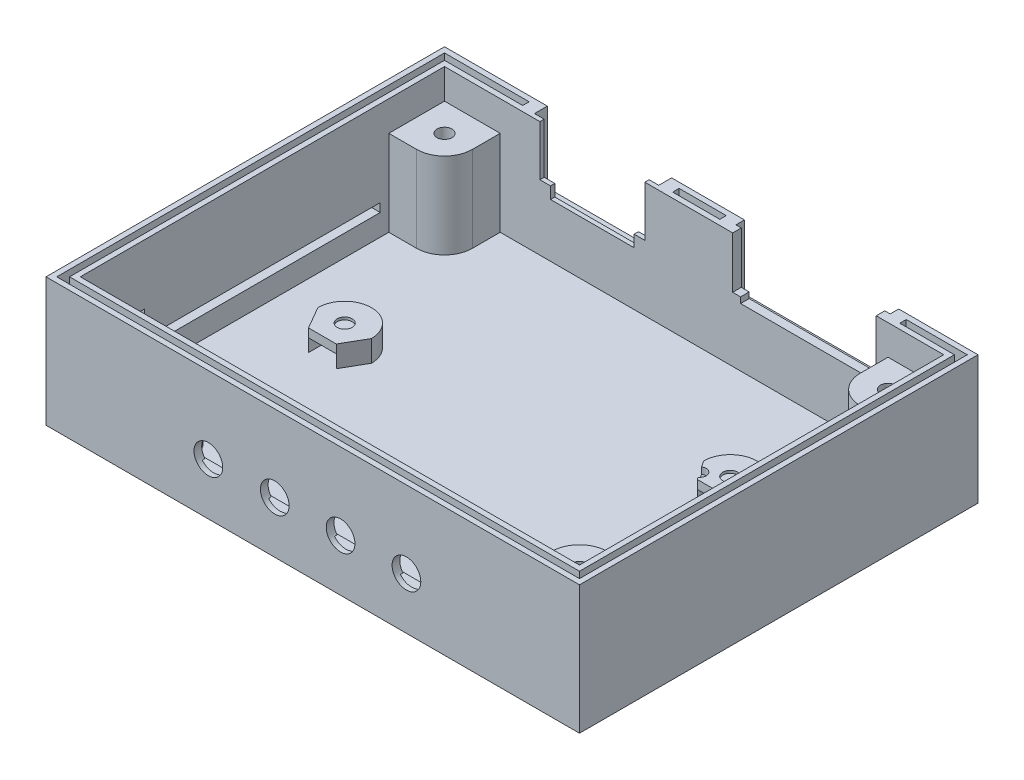
SolidWorks part; units mm, degrees
ref_plane "Спереди" through (0, 0, 0) normal (0, 0, 1) x (1, 0, 0)
ref_plane "Сверху" through (0, 0, 0) normal (0, 1, 0) x (1, 0, 0)
ref_plane "Справа" through (0, 0, 0) normal (1, 0, 0) x (0, 0, -1)
sketch "Эскиз1" plane through (0, 0, 0) normal (0, 1, 0) x (1, 0, 0)
  line L1 (-58.25, -42.5) -> (58.25, -42.5)
  line L2 (-58.25, -42.5) -> (-58.25, 42.5)
  line L3 (-58.25, 42.5) -> (58.25, 42.5)
  line L4 (58.25, -42.5) -> (58.25, 42.5)
  line L5 (-58.25, -42.5) -> (58.25, 42.5) construction
  line L6 (-58.25, 42.5) -> (58.25, -42.5) construction
  point P0 (0, 0)
  dimension "D1" = 116.5
  dimension "D2" = 85
extrude "Бобышка-Вытянуть1" add sketch "Эскиз1" along normal blind 3
sketch "Эскиз3" plane through (0, 3, 0) normal (0, 1, 0) x (1, 0, 0)
  line L0 (-58.25, 42.5) -> (-58.25, -42.5) construction
  line L1 (-36.8, -40.5) -> (-38.425, -37.6854) construction
  line L2 (-38.425, -37.6854) -> (-41.675, -37.6854) construction
  line L3 (-41.675, -37.6854) -> (-43.3, -40.5) construction
  line L4 (-43.3, -40.5) -> (-41.675, -43.3146) construction
  line L5 (-41.675, -43.3146) -> (-38.425, -43.3146) construction
  line L6 (-38.425, -43.3146) -> (-36.8, -40.5) construction
  line L7 (-58.25, -42.5) -> (58.25, -42.5) construction
  line L8 (-46.3, -40.5) -> (-46.3, -42.5)
  line L9 (-46.3, -40.5) -> (-43.3, -35.3038)
  line L10 (-33.8, -42.5) -> (-33.8, -40.5)
  line L11 (-43.3, -35.3038) -> (-43.3, -40.5)
  line L12 (-43.3, -40.5) -> (-91.5414, -40.5) construction
  line L13 (-33.8, -40.5) -> (-36.8, -40.5) construction
  line L14 (-36.8, -40.5) -> (-36.8, -35.3038)
  line L15 (-33.8, -40.5) -> (-36.8, -35.3038)
  line L19 (32.7, -40.5) -> (34.325, -43.3146) construction
  line L21 (34.325, -43.3146) -> (37.575, -43.3146) construction
  line L22 (37.575, -43.3146) -> (39.2, -40.5) construction
  line L23 (39.2, -40.5) -> (39.2, -35.3038)
  line L31 (-43.3, 1) -> (-46.3, 1) construction
  line L32 (-36.8, 1) -> (-38.425, 3.8146)
  line L33 (-38.425, 3.8146) -> (-41.675, 3.8146)
  line L34 (-41.675, 3.8146) -> (-43.3, 1)
  line L35 (-43.3, 1) -> (-41.675, -1.8146) construction
  line L36 (-41.675, -1.8146) -> (-38.425, -1.8146) construction
  line L37 (-38.425, -1.8146) -> (-36.8, 1) construction
  line L38 (-40.05, 3.8146) -> (-40.05, -1.8146) construction
  line L39 (-46.3, 1) -> (-43.3, -4.1962)
  line L40 (-43.3, -4.1962) -> (-43.3, 1)
  line L41 (-36.8, 1) -> (-33.8, 1) construction
  line L42 (-33.8, 1) -> (-36.8, -4.1962)
  line L43 (-36.8, -4.1962) -> (-36.8, 1)
  line L44 (35.95, 15) -> (-41.0381, 65.945) construction
  line L57 (42.2, -40.5) -> (39.2, -35.3038)
  line L58 (42.2, -42.5) -> (42.2, -40.5)
  line L60 (29.7, -40.5) -> (29.7, -42.5)
  line L61 (29.7, -40.5) -> (32.7, -35.3038)
  line L62 (32.7, -35.3038) -> (32.7, -40.5)
  line L67 (-46.3, -42.5) -> (-42.1453, -42.5)
  line L68 (-33.8, -42.5) -> (-37.9547, -42.5)
  line L69 (-42.1453, -42.5) -> (-43.3, -40.5)
  line L70 (-37.9547, -42.5) -> (-36.8, -40.5)
  line L71 (29.7, -42.5) -> (33.8547, -42.5)
  line L72 (42.2, -42.5) -> (38.0453, -42.5)
  line L73 (33.8547, -42.5) -> (32.7, -40.5)
  line L74 (38.0453, -42.5) -> (39.2, -40.5)
  line L76 (32.7, 15) -> (29.7, 15) construction
  line L77 (39.2, 15) -> (37.3861, 17.6967)
  line L78 (37.3861, 17.6967) -> (34.5139, 17.6967)
  line L79 (34.5139, 17.6967) -> (32.7, 15)
  line L80 (32.7, 15) -> (34.5139, 12.3033) construction
  line L81 (34.5139, 12.3033) -> (37.3861, 12.3033) construction
  line L82 (37.3861, 12.3033) -> (39.2, 15) construction
  line L83 (35.95, 17.6967) -> (35.95, 12.3033) construction
  line L84 (29.7, 15) -> (32.7, 10.5398)
  line L85 (32.7, 10.5398) -> (32.7, 15)
  line L86 (39.2, 15) -> (42.2, 15) construction
  line L87 (42.2, 15) -> (39.2, 10.5398)
  line L88 (39.2, 10.5398) -> (39.2, 15)
  line L89 (32.7, 10.5398) -> (19.4042, 10.5398) construction
  circle A0 centre (-40.05, -40.5) radius 2.8146 construction
  circle A2 centre (-40.05, 1) radius 2.8146 construction
  circle A4 centre (35.95, 15) radius 2.6967 construction
  arc A6 (-46.3, 1) -> (-33.8, 1) centre (-40.05, 1) cw
  arc A7 (29.7, 15) -> (42.2, 15) centre (35.95, 15) cw
  dimension "D1" = 6.5
  dimension "D17" = 6.25
  dimension "D18" = 6.25
  dimension "D2" = 18.2
  dimension "D3" = 2
  dimension "D4" = 3
  dimension "D5" = 3
  dimension "D7" = 18.2
  dimension "D8" = 43.5
  dimension "D9" = 6.5
  dimension "D10" = 3
  dimension "D11" = 3
  dimension "D12" = 57.5
  dimension "D13" = 94.2
  dimension "D14" = 6.5
  dimension "D15" = 3
  dimension "D16" = 3
  dimension "D6" = 2
extrude "Бобышка-Вытянуть2" add sketch "Эскиз3" along normal blind 3
sketch "Эскиз4" plane through (0, 6, 0) normal (0, 1, 0) x (1, 0, 0)
  line L2 (-33.8, -40.5) -> (-36.8, -35.3038)
  line L3 (-36.8, -35.3038) -> (-43.3, -35.3038)
  line L4 (-43.3, -35.3038) -> (-46.3, -40.5)
  line L6 (-46.3, 1) -> (-43.3, -4.1962)
  line L7 (-43.3, -4.1962) -> (-36.8, -4.1962)
  line L8 (-36.8, -4.1962) -> (-33.8, 1)
  line L9 (29.7, 15) -> (32.7, 10.5398)
  line L10 (32.7, 10.5398) -> (39.2, 10.5398)
  line L11 (39.2, 10.5398) -> (42.2, 15)
  line L12 (29.7, -40.5) -> (29.7, -42.5)
  line L15 (42.2, -40.5) -> (39.2, -35.3038)
  line L16 (39.2, -35.3038) -> (32.7, -35.3038)
  line L17 (32.7, -35.3038) -> (29.7, -40.5)
  line L18 (32.7, -40.5) -> (39.2, -40.5) construction
  line L19 (-43.3, -40.5) -> (-36.8, -40.5) construction
  line L25 (-46.3, -40.5) -> (-46.3, -42.5)
  line L26 (-46.3, -42.5) -> (-33.8, -42.5)
  line L27 (-33.8, -42.5) -> (-33.8, -40.5)
  line L28 (29.7, -42.5) -> (42.2, -42.5)
  line L29 (42.2, -42.5) -> (42.2, -40.5)
  line L30 (29.7, 15) -> (42.2, 15) construction
  line L31 (-46.3, 1) -> (-33.8, 1) construction
  line L32 (-36.8, 1) -> (-36.8, -4.1962) construction
  arc A0 (-46.3, 1) -> (-33.8, 1) centre (-40.05, 1) cw
  arc A1 (29.7, 15) -> (42.2, 15) centre (35.95, 15) cw
  circle A2 centre (35.95, -40.5) radius 1.6 construction
  circle A3 centre (35.95, 15) radius 1.6 construction
  circle A4 centre (-40.05, 1) radius 1.6 construction
  circle A5 centre (-40.05, -40.5) radius 1.6 construction
  arc A7 (-33.8, 1) -> (-46.3, 1) centre (-40.05, 1) ccw construction
  point P2 (-36.8, -4.1962)
  dimension "D1" = 3.2
extrude "Бобышка-Вытянуть3" add sketch "Эскиз4" along normal blind 2
sketch3d "Трехмерный эскиз1"
  line L0 (-60.05, 3, 45) -> (-52.2057, 3, 31.4133)
  line L1 (-58.25, 3, 42.5) -> (-46.3, 3, 42.5) construction
  line L2 (-60.05, 3, 50.197) -> (-60.05, 3, 53.4146) construction
  line L4 (-58.25, 3, -42.5) -> (-58.25, 3, 42.5) construction
  dimension "D1" = 60
  dimension "D2" = 1.8
  dimension "D3" = 2.5
ref_plane "Плоскость1" through (-25.5519, 0, -14.7524) normal (0.866, 0, 0.5) x (0.5, 0, -0.866)
sketch "Эскиз5" plane through (0, 8, 0) normal (0, 1, 0) x (1, 0, 0)
  line L1 (-33.8, -40.5) -> (-36.8, -35.3038) construction
  line L2 (-35.8, -37.0359) -> (-33.8, -37.0359)
  line L3 (-33.8, -37.0359) -> (-33.8, -42.5)
  line L5 (35.7, -35.3038) -> (35.7, -36.8038)
  line L6 (39.2, -35.3038) -> (32.7, -35.3038) construction
  line L7 (35.7, -36.8038) -> (37.2, -36.8038)
  line L8 (37.2, -36.8038) -> (37.2, -35.3038)
  line L9 (37.2, -35.3038) -> (35.7, -35.3038)
  line L10 (29.7, 15) -> (32.7, 10.5398) construction
  line L11 (30.6656, 13.5644) -> (32.3399, 11.0751)
  line L12 (-35.8, -37.0359) -> (-35.8, -42.5)
  line L13 (-46.3, -42.5) -> (-33.8, -42.5) construction
  line L14 (-35.8, -42.5) -> (-33.8, -42.5)
  arc A0 (30.6656, 13.5644) -> (32.3399, 11.0751) centre (31.5027, 12.3198) cw
  point P0 (-35.8, -37.0359)
  dimension "D5" = 1.5
  dimension "D1" = 2
  dimension "D2" = 1.5
  dimension "D3" = 2
  dimension "D4" = 1.78
  dimension "D6" = 0
  dimension "D7" = 1.5
extrude "Вырез-Вытянуть1" cut sketch "Эскиз5" against normal blind 1.5
sketch "Эскиз211" plane through (0, 8, 0) normal (0, 1, 0) x (1, 0, 0)
  line L0 (29.7, -40.5) -> (42.2, -40.5) construction
  line L1 (-46.3, -40.5) -> (-33.8, -40.5) construction
  circle A0 centre (-40.05, 1) radius 1.75
  circle A1 centre (35.95, 15) radius 1.75
  circle A2 centre (35.95, -40.5) radius 1.75
  circle A3 centre (-40.05, -40.5) radius 1.75
  point P18 (42.2, -40.5)
  point P20 (-33.8, -40.5)
  dimension "D1" = 3.5
  dimension "D2" = 3.5
  dimension "D3" = 3.5
  dimension "D4" = 3.5
extrude "Вырез-Вытянуть17" cut sketch "Эскиз211" against normal blind 0.6
sketch "Эскиз6" plane through (0, 3, 0) normal (0, 1, 0) x (1, 0, 0)
  line L2 (58.25, -42.5) -> (58.25, 42.5)
  line L3 (58.25, 42.5) -> (-58.25, 42.5)
  line L5 (-58.25, -42.5) -> (58.25, -42.5)
  line L6 (-58.25, 42.5) -> (-58.25, -42.5)
extrude "Вытянуть-Тонкостенный1" add sketch "Эскиз6" along normal blind 27 and the other way blind 3 thin
sketch "Эскиз29" plane through (0, 3, 0) normal (0, 1, 0) x (1, 0, 0)
  line L0 (-35.8, -37.0359) -> (-36.8, -35.3038) construction
  line L1 (-36.8, -40.5) -> (-38.425, -37.6854)
  line L2 (-38.425, -37.6854) -> (-41.675, -37.6854)
  line L3 (-41.675, -37.6854) -> (-43.3, -40.5)
  line L4 (-43.3, -40.5) -> (-41.675, -43.3146)
  line L5 (-41.675, -43.3146) -> (-38.425, -43.3146)
  line L6 (-38.425, -43.3146) -> (-36.8, -40.5)
  line L7 (39.2, -40.5) -> (37.575, -37.6854)
  line L8 (37.575, -37.6854) -> (34.325, -37.6854)
  line L9 (34.325, -37.6854) -> (32.7, -40.5)
  line L10 (32.7, -40.5) -> (34.325, -43.3146)
  line L11 (34.325, -43.3146) -> (37.575, -43.3146)
  line L12 (37.575, -43.3146) -> (39.2, -40.5)
  line L13 (-43.3, -35.3038) -> (-46.3, -40.5) construction
  line L15 (42.2, -40.5) -> (39.2, -35.3038) construction
  line L16 (32.7, -35.3038) -> (29.7, -40.5) construction
  circle A0 centre (-40.05, -40.5) radius 2.8146 construction
  circle A1 centre (35.95, -40.5) radius 2.8146 construction
  dimension "D1" = 6.5
  dimension "D2" = 6.5
  dimension "D3" = 2.5981
  dimension "D4" = 2.5981
  dimension "D5" = 2.5981
  dimension "D6" = 2.5981
extrude "Вырез-Вытянуть6" cut sketch "Эскиз29" along normal blind 3
ref_plane "Плоскость2" through (0, 8, 0) normal (0, 1, 0) x (1, 0, 0)
sketch "Эскиз9" plane through (0, 8, 0) normal (0, 1, 0) x (1, 0, 0)
  line L0 (-58.25, -42.5) -> (46.75, -42.5)
  line L2 (-58.25, -42.5) -> (-58.25, 27.5)
  line L4 (-60.05, 199949.803) -> (-60.05, -200053.4146) construction
  line L5 (42.2, -42.5) -> (58.25, -42.5) construction
  dimension "D1" = 105
  dimension "D2" = 70
extrude "Вырез-Вытянуть-Тонкостенный1" cut sketch "Эскиз9" along normal blind 2 thin
sketch "Эскиз30" plane through (0, 0, 42.5) normal (0, 0, -1) x (-1, 0, 0)
  line L0 (58.25, 12.1) -> (33.0029, 12.1) construction
  line L2 (58.25, 3) -> (46.3, 3) construction
  line L3 (58.25, 10) -> (58.25, 30) construction
  circle A0 centre (24.363, 12.1) radius 3.35
  circle A1 centre (8.869, 12.1) radius 3.35
  circle A2 centre (-6.498, 12.1) radius 3.35
  circle A3 centre (-21.865, 12.1) radius 3.35
  dimension "D2" = 6.7
  dimension "D4" = 6.7
  dimension "D8" = 6.7
  dimension "D9" = 6.7
  dimension "D1" = 9.1
  dimension "D3" = 33.887
  dimension "D5" = 49.381
  dimension "D6" = 64.748
  dimension "D7" = 80.115
extrude "Вырез-Вытянуть7" cut sketch "Эскиз30" against normal up to surface (4 mm away) up to face at (0, 15, 46.5)
sketch "Эскиз31" plane through (0, 0, 42.5) normal (0, 0, -1) x (-1, 0, 0)
  line L1 (17.763, 8.6) -> (30.963, 8.6)
  line L2 (17.763, 8.6) -> (17.763, 15.6)
  line L3 (17.763, 15.6) -> (30.963, 15.6)
  line L4 (30.963, 8.6) -> (30.963, 15.6)
  line L5 (17.763, 8.6) -> (30.963, 15.6) construction
  line L6 (17.763, 15.6) -> (30.963, 8.6) construction
  line L7 (2.269, 8.6) -> (15.469, 8.6)
  line L8 (2.269, 8.6) -> (2.269, 15.6)
  line L9 (2.269, 15.6) -> (15.469, 15.6)
  line L10 (15.469, 8.6) -> (15.469, 15.6)
  line L11 (2.269, 8.6) -> (15.469, 15.6) construction
  line L12 (2.269, 15.6) -> (15.469, 8.6) construction
  line L13 (-13.098, 8.6) -> (0.102, 8.6)
  line L14 (-13.098, 8.6) -> (-13.098, 15.6)
  line L15 (-13.098, 15.6) -> (0.102, 15.6)
  line L16 (0.102, 8.6) -> (0.102, 15.6)
  line L17 (-13.098, 8.6) -> (0.102, 15.6) construction
  line L18 (-13.098, 15.6) -> (0.102, 8.6) construction
  line L19 (-28.465, 8.6) -> (-15.265, 8.6)
  line L20 (-28.465, 8.6) -> (-28.465, 15.6)
  line L21 (-28.465, 15.6) -> (-15.265, 15.6)
  line L22 (-15.265, 8.6) -> (-15.265, 15.6)
  line L23 (-28.465, 8.6) -> (-15.265, 15.6) construction
  line L24 (-28.465, 15.6) -> (-15.265, 8.6) construction
  point P0 (24.363, 12.1)
  point P6 (8.869, 12.1)
  point P12 (-6.498, 12.1)
  point P18 (-21.865, 12.1)
  dimension "D1" = 13.2
  dimension "D2" = 13.2
  dimension "D3" = 13.2
  dimension "D4" = 13.2
  dimension "D5" = 7
  dimension "D6" = 7
  dimension "D7" = 7
  dimension "D8" = 7
extrude "Вырез-Вытянуть8" cut sketch "Эскиз31" against normal blind 2.2
sketch3d "Трехмерный эскиз3"
  line L0 (-12.2167, 12.2244, 46.5) -> (-8.869, 12.1, 46.5) construction
  line L1 (-24.363, 12.1, 46.5) -> (-27.7109, 12.2198, 46.5) construction
  line L2 (-24.363, 12.1, 44.57) -> (-18.4622, 12.1, 34.3495)
  line L3 (20.737, 12.1, 46.5) -> (-69.463, 12.1, 46.5) construction
  line L4 (-24.363, 12.1, 46.5) -> (-24.363, 12.1, 47.1668) construction
  line L5 (-8.869, 12.1, 45.3) -> (-8.869, 12.1, 44.7) construction
  line L6 (-8.869, 12.1, 44.57) -> (-2.4822, 12.1, 33.5078)
  line L9 (-27.7053, 12.3268, 46.5) -> (-24.363, 12.1, 46.5) construction
  line L10 (-24.363, 12.1, 45.3) -> (-24.363, 12.1, 44.7) construction
  line L11 (-24.363, 12.1, 44.57) -> (-21.013, 12.1, 46.5) construction
  line L12 (-8.869, 12.1, 46.5) -> (-8.869, 12.1, 45.6691) construction
  line L13 (3.1501, 12.2183, 46.5) -> (6.498, 12.1, 46.5) construction
  line L14 (6.498, 12.1, 45.3) -> (6.498, 12.1, 44.7) construction
  line L15 (18.5183, 12.2495, 46.5) -> (21.865, 12.1, 46.5) construction
  line L16 (21.865, 12.1, 45.3) -> (21.865, 12.1, 44.7) construction
  line L17 (6.498, 12.1, 46.5) -> (6.498, 12.1, 44.57) construction
  line L18 (21.865, 12.1, 46.5) -> (21.865, 12.1, 44.57) construction
  line L19 (6.498, 12.1, 44.57) -> (11.4556, 12.1, 35.9831)
  line L20 (21.865, 12.1, 44.57) -> (26.1469, 12.1, 37.1535)
  circle A0 centre (-24.363, 12.1, 46.5) radius 3.35 construction
  circle A1 centre (-8.869, 12.1, 46.5) radius 3.35 construction
  circle A2 centre (6.498, 12.1, 46.5) radius 3.35 construction
  circle A3 centre (21.865, 12.1, 46.5) radius 3.35 construction
  point P10 (-24.363, 12.1, 43.15)
  point P14 (-8.869, 12.1, 43.15)
  point P28 (6.498, 12.1, 43.15)
  point P35 (21.865, 12.1, 43.15)
  point P42 (0, 0, 0)
  point P43 (0.8434, 12.1, 36.2693)
  point P44 (13.0277, 12.1, 37.1042)
  point P45 (27.6053, 12.1, 38.2107)
  point P46 (-24.363, 12.1, 43.9721)
  point P47 (-18.7221, 12.1, 34.2038)
  dimension "D1" = 1.93
  dimension "D3" = 60
  dimension "D2" = 0
  dimension "D4" = 60
  dimension "D6" = 60
  dimension "D5" = 3.35
  dimension "D7" = 1.93
  dimension "D8" = 1.93
  dimension "D9" = 1.93
  dimension "D10" = 60
sweep "Вырез-По траектории1" cut path "Трехмерный эскиз3" circular profile diameter 7.7 parameters "D3"=7.7
curve "Кривая1"
sweep "Вырез-По траектории3" cut path "Кривая1" circular profile diameter 7.7 parameters "D3"=7.7
curve "Кривая2"
curve "Кривая3"
sweep "Вырез-По траектории4" cut path "Кривая2" circular profile diameter 7.7 parameters "D3"=7.7
sweep "Вырез-По траектории5" cut path "Кривая3" circular profile diameter 7.7 parameters "D3"=7.7
sketch "Эскиз121" plane through (-58.25, 0, 0) normal (1, 0, 0) x (0, 0, -1)
  line L0 (-42.5, 12.1) -> (-38.102, 12.1) construction
  line L1 (-42.5, 10) -> (-42.5, 30) construction
  line L2 (42.5, 3) -> (-42.5, 3) construction
  circle A0 centre (-38.102, 12.1) radius 3.35
  dimension "D1" = 9.1
  dimension "D3" = 6.7
  dimension "D2" = 4.398
extrude "Вырез-Вытянуть11" cut sketch "Эскиз121" against normal up to surface (4 mm away) up to face at (-62.25, 15, 0)
sketch3d "Трехмерный эскиз4"
  line L0 (-62.25, 13.1301, 41.2897) -> (-62.25, 12.1, 38.102) construction
  line L1 (-61.05, 12.1, 38.102) -> (-58.25, 12.1, 38.102) construction
  line L2 (-62.25, 12.1, 38.102) -> (-93.9842, 12.1, 38.102) construction
  line L3 (-60.32, 12.1, 38.102) -> (-47.3296, 12.1, 30.602)
  circle A0 centre (-62.25, 12.1, 38.102) radius 3.35 construction
  point P4 (-58.9, 12.1, 38.102)
  dimension "D1" = 150
  dimension "D2" = 1.93
  dimension "D3" = 15
sweep "Вырез-По траектории6" cut path "Трехмерный эскиз4" circular profile diameter 6.7 parameters "D3"=6.7
sketch "Эскиз143" plane through (0, 8, 0) normal (0, 1, 0) x (1, 0, 0)
  line L0 (-58.25, -42.5) -> (-58.25, -27.5)
  line L1 (-58.25, -42.5) -> (-58.25, 27.5) construction
  line L2 (-58.25, -42.5) -> (-46.25, -42.5)
  line L3 (-46.3, -42.5) -> (-58.25, -42.5) construction
  dimension "D1" = 12
  dimension "D2" = 15
extrude "Вырез-Вытянуть-Тонкостенный2" cut sketch "Эскиз143" along normal blind 8 thin thin type one direction wall 2
sketch "Эскиз149" plane through (0, 0, -46.5) normal (0, 0, -1) x (-1, 0, 0)
  line L0 (38.25, 30) -> (38.25, 0) construction
  line L1 (-62.25, 30) -> (62.25, 30) construction
  line L2 (-62.25, 0) -> (62.25, 0) construction
  line L3 (62.25, 0) -> (62.25, 30) construction
  line L5 (38.25, 30) -> (9.25, 30)
  line L6 (38.25, 30) -> (38.25, 13.5)
  line L7 (38.25, 13.5) -> (9.25, 13.5)
  line L8 (9.25, 30) -> (9.25, 13.5)
  dimension "D1" = 24
  dimension "D2" = 16.5
  dimension "D3" = 29
extrude "Вырез-Вытянуть12" cut sketch "Эскиз149" against normal blind 3
sketch "Эскиз150" plane through (0, 0, -43.5) normal (0, 0, -1) x (-1, 0, 0)
  line L0 (9.25, 21.75) -> (38.25, 21.75) construction
  line L1 (9.25, 30) -> (9.25, 13.5) construction
  line L2 (38.25, 13.5) -> (38.25, 30) construction
  line L4 (11.5, 18.25) -> (14, 18.25)
  line L5 (14, 18.25) -> (14, 15.5)
  line L7 (23.75, 30) -> (23.75, 13.5) construction
  line L8 (38.25, 30) -> (9.25, 30) construction
  line L9 (9.25, 13.5) -> (38.25, 13.5) construction
  line L13 (33.5, 18.25) -> (33.5, 15.5)
  line L14 (36, 18.25) -> (33.5, 18.25)
  line L18 (14, 15.5) -> (33.5, 15.5)
  line L19 (11.5, 18.25) -> (11.5, 30)
  line L20 (11.5, 30) -> (36, 30)
  line L21 (36, 18.25) -> (36, 30)
  point P18 (23.75, 15.5)
  point P20 (23.75, 15.5)
  dimension "D1" = 9.75
  dimension "D2" = 6.25
  dimension "D3" = 3.5
  dimension "D4" = 12.25
extrude "Вырез-Вытянуть13" cut sketch "Эскиз150" against normal up to surface (1 mm away) up to face at (0, 16.5, -42.5)
sketch "Эскиз191" plane through (0, 0, -46.5) normal (0, 0, -1) x (-1, 0, 0)
  line L0 (-7.75, 30) -> (-7.75, 0) construction
  line L1 (-62.25, 30) -> (9.25, 30) construction
  line L2 (-62.25, 0) -> (62.25, 0) construction
  line L3 (62.25, 0) -> (62.25, 30) construction
  line L5 (-7.75, 30) -> (-43.75, 30)
  line L6 (-7.75, 30) -> (-7.75, 15)
  line L7 (-7.75, 15) -> (-43.75, 15)
  line L8 (-43.75, 30) -> (-43.75, 15)
  dimension "D1" = 70
  dimension "D2" = 36
  dimension "D3" = 15
extrude "Вырез-Вытянуть14" cut sketch "Эскиз191" against normal blind 2
sketch "Эскиз192" plane through (0, 0, -44.5) normal (0, 0, -1) x (-1, 0, 0)
  line L0 (-25.75, 30) -> (-25.75, 15) construction
  line L1 (-7.75, 30) -> (-43.75, 30) construction
  line L2 (-43.75, 15) -> (-7.75, 15) construction
  line L3 (-43.75, 22.5) -> (-7.75, 22.5) construction
  line L4 (-43.75, 30) -> (-43.75, 15) construction
  line L5 (-7.75, 15) -> (-7.75, 30) construction
  line L6 (-42.5, 30) -> (-42.5, 18)
  line L7 (-42.5, 18) -> (-40.65, 18)
  line L8 (-40.65, 18) -> (-40.65, 16.65)
  line L9 (-40.65, 16.65) -> (-10.85, 16.65)
  line L10 (-10.85, 18) -> (-10.85, 16.65)
  line L11 (-9, 18) -> (-10.85, 18)
  line L12 (-9, 30) -> (-9, 18)
  line L13 (-42.5, 30) -> (-9, 30)
  point P18 (-25.75, 16.65)
  dimension "D1" = 5.85
  dimension "D2" = 4.5
  dimension "D3" = 14.9
  dimension "D4" = 16.75
extrude "Вырез-Вытянуть15" cut sketch "Эскиз192" against normal up to surface (2 mm away) up to face at (-15.8333, 19.1667, -42.5)
sketch "Эскиз193" plane through (0, 3, 0) normal (0, 1, 0) x (1, 0, 0)
  line L0 (-58.25, 42.5) -> (-58.25, -42.5) construction
  line L1 (58.25, -42.5) -> (58.25, -29.5)
  line L2 (58.25, 42.5) -> (-58.25, 42.5) construction
  line L3 (-51.75, 36) -> (-58.25, 36) construction
  line L4 (-51.75, 36) -> (-51.75, 42.5) construction
  line L7 (-51.75, 29.5) -> (-58.25, 29.5)
  line L10 (58.25, -42.5) -> (58.25, 42.5) construction
  line L11 (-36, 42.5) -> (-58.25, 42.5) construction
  line L12 (-45.25, 42.5) -> (-45.25, 36)
  line L13 (51.75, 42.5) -> (51.75, 24.4181) construction
  line L14 (45.25, 36) -> (45.25, 42.5)
  line L15 (45.25, 42.5) -> (58.25, 42.5)
  line L17 (64.5444, -36) -> (43.6647, -36) construction
  line L18 (-58.25, -42.5) -> (58.25, -42.5) construction
  line L19 (45.25, -36) -> (45.25, -42.5)
  line L20 (45.25, -42.5) -> (58.25, -42.5)
  line L22 (58.25, -29.5) -> (51.75, -29.5)
  line L23 (58.25, 42.5) -> (58.25, 29.5)
  line L24 (58.25, -42.5) -> (58.25, 42.5) construction
  line L25 (58.25, 29.5) -> (51.75, 29.5)
  line L26 (-58.25, 29.5) -> (-58.25, 42.5)
  line L27 (-58.25, 42.5) -> (-45.25, 42.5)
  circle A0 centre (-51.75, 36) radius 4 construction
  circle A1 centre (-51.75, 36) radius 6.5 construction
  arc A3 (-45.25, 36) -> (-51.75, 29.5) centre (-51.75, 36) cw
  arc A4 (45.25, 36) -> (51.75, 29.5) centre (51.75, 36) ccw
  arc A5 (45.25, -36) -> (51.75, -29.5) centre (51.75, -36) cw
  dimension "D1" = 8
  dimension "D2" = 13
  dimension "D6" = 6.5
  dimension "D8" = 6.5
  dimension "D3" = 6.5
  dimension "D4" = 6.5
  dimension "D5" = 110
  dimension "D7" = 6.5
extrude "Бобышка-Вытянуть4" add sketch "Эскиз193" along normal blind 20
sketch "Эскиз194" plane through (0, 23, 0) normal (0, 1, 0) x (1, 0, 0)
  circle A0 centre (-51.75, 36) radius 1.75
  circle A1 centre (51.75, 36) radius 1.75
  circle A2 centre (51.75, -36) radius 1.75
  dimension "D1" = 3.5
  dimension "D2" = 3.5
  dimension "D3" = 3.5
extrude "Вырез-Вытянуть16" cut sketch "Эскиз194" against normal blind 10
sketch "Эскиз238" plane through (0, 30, 0) normal (0, 1, 0) x (1, 0, 0)
  line L0 (-58.25, -42.5) -> (-62.25, -42.5) construction
  line L1 (-62.25, 46.5) -> (-62.25, -46.5) construction
  line L2 (-58.25, -42.5) -> (-58.25, -46.5) construction
  line L3 (-62.25, -46.5) -> (62.25, -46.5) construction
  line L4 (-58.25, 42.5) -> (-58.25, 46.5) construction
  line L5 (-38.25, 46.5) -> (-62.25, 46.5) construction
  line L6 (58.25, 42.5) -> (62.25, 42.5) construction
  line L7 (62.25, -46.5) -> (62.25, 46.5) construction
  line L8 (60.25, 42.5) -> (60.25, 32.1797) construction
  line L9 (-59.0271, -44.5) -> (-55.3718, -44.5) construction
  line L10 (-60.25, -42.5) -> (-60.25, -38.0571) construction
  line L11 (-59.0271, 44.5) -> (-52.0048, 44.5) construction
  line L12 (-60.25, -44.5) -> (60.25, -44.5)
  line L13 (60.25, -44.5) -> (60.25, 44.5)
  line L14 (60.25, 44.5) -> (46.75, 44.5)
  line L15 (4.75, 44.5) -> (-6.25, 44.5)
  line L16 (-41.25, 44.5) -> (-60.25, 44.5)
  line L17 (-60.25, 44.5) -> (-60.25, -44.5)
  line L18 (-38.25, 43.5) -> (-38.25, 46.5) construction
  line L19 (-9.25, 43.5) -> (-9.25, 46.5) construction
  line L20 (7.75, 44.5) -> (7.75, 46.5) construction
  line L21 (43.75, 44.5) -> (43.75, 46.5) construction
  line L22 (62.25, 46.5) -> (43.75, 46.5) construction
  dimension "D1" = 3
  dimension "D2" = 3
  dimension "D3" = 3
  dimension "D4" = 3
  dimension "D5" = 2
  dimension "D6" = 2
  dimension "D7" = 2
  dimension "D8" = 2
extrude "Вырез-Вытянуть-Тонкостенный3" cut sketch "Эскиз238" against normal blind 3 thin thin type mid plane wall 1.5
equation "\"D1@Эскиз30\"=1.6+3+2+2.5"
equation "\"D4@Эскиз30\"=\"D2@Эскиз30\""
equation "\"D8@Эскиз30\"=\"D2@Эскиз30\""
equation "\"D9@Эскиз30\"=\"D2@Эскиз30\""
equation "\"D3@Эскиз30\"=35.687-1.8мм"
equation "\"D5@Эскиз30\"=51.181-1.8мм"
equation "\"D6@Эскиз30\"=66.548-1.8мм"
equation "\"D7@Эскиз30\"=81.915-1.8мм"
equation "\"D2@Эскиз31\"=\"D1@Эскиз31\""
equation "\"D3@Эскиз31\"=\"D1@Эскиз31\""
equation "\"D4@Эскиз31\"=\"D1@Эскиз31\""
equation "\"D5@Эскиз31\"=7"
equation "\"D6@Эскиз31\"=\"D5@Эскиз31\""
equation "\"D7@Эскиз31\"=\"D5@Эскиз31\""
equation "\"D8@Эскиз31\"=\"D5@Эскиз31\""
equation "\"D2@Эскиз29\"=\"D1@Эскиз29\""
equation "\"D2@Эскиз3\"=20.00-1.8мм"
equation "\"D7@Эскиз3\"=\"D2@Эскиз3\""
equation "\"D2@Эскиз121\"=6.898-2.5мм"
equation "\"D13@Эскиз3\"=96.0-1.80мм"
equation "\"D2@Эскиз194\"=\"D1@Эскиз194\""
equation "\"D3@Эскиз194\"=\"D2@Эскиз194\""
equation "\"D2@Эскиз211\"=\"D1@Эскиз211\""
equation "\"D3@Эскиз211\"=\"D1@Эскиз211\""
equation "\"D4@Эскиз211\"=\"D1@Эскиз211\""
